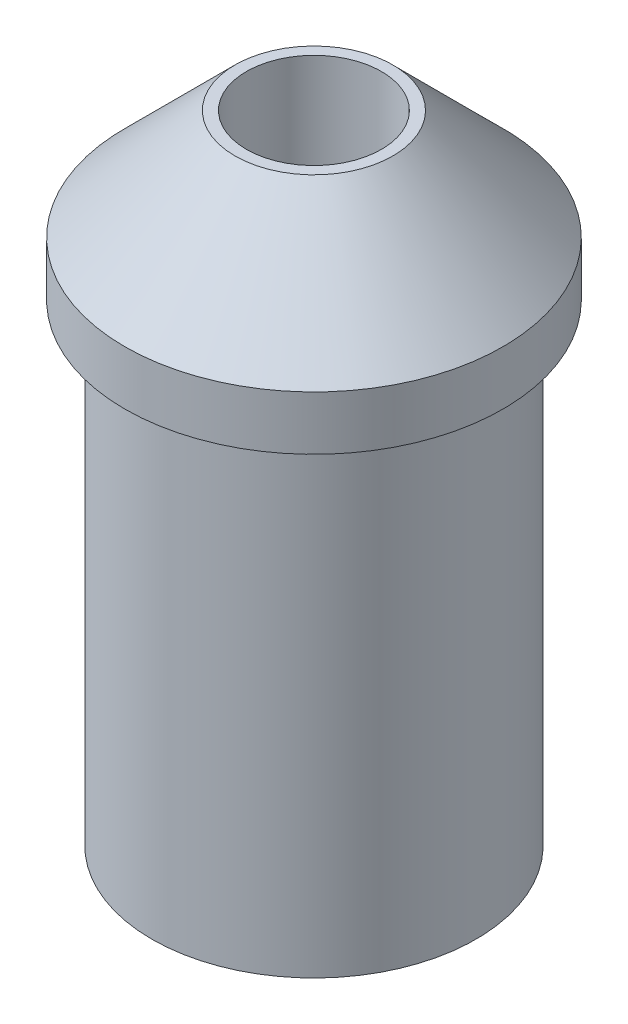
SolidWorks part; units mm, degrees
ref_plane "Front Plane" through (0, 0, 0) normal (0, 0, 1) x (1, 0, 0)
ref_plane "Top Plane" through (0, 0, 0) normal (0, 1, 0) x (1, 0, 0)
ref_plane "Right Plane" through (0, 0, 0) normal (1, 0, 0) x (0, 0, -1)
sketch "Sketch2" plane through (0, 0, 0) normal (0, 1, 0) x (1, 0, 0)
  circle A0 centre (0, 0) radius 3
  dimension "D1" = 6
extrude "Boss-Extrude1" add sketch "Sketch2" against normal blind 8.75
sketch "Sketch5" plane through (0, 0, 0) normal (0, 1, 0) x (1, 0, 0)
  circle A0 centre (0, 0) radius 3.5
  dimension "D1" = 7
extrude "Boss-Extrude4" add sketch "Sketch5" along normal blind 1
sketch "Sketch6" plane through (0, 0, 0) normal (0, 0, 1) x (1, 0, 0)
  line L0 (-3.5, 1) -> (-1.4611, 3.0389)
  line L1 (-1.4611, 3.0389) -> (-1.25, 3.0389)
  line L2 (-1.25, 3.0389) -> (-1.25, 1)
  line L3 (3.5, 1) -> (-3.5, 1) construction
  line L4 (-1.25, 1) -> (-3.5, 1)
  line L5 (-1.25, 3.0389) -> (0, 3.0389) construction
  line L6 (0, 3.0389) -> (1.25, 3.0389) construction
  line L7 (0, 3.0389) -> (0, 1) construction
  dimension "D1" = 2.5
  dimension "D2" = 45
revolve "Revolve1" add sketch "Sketch6" angle 360 about L7
